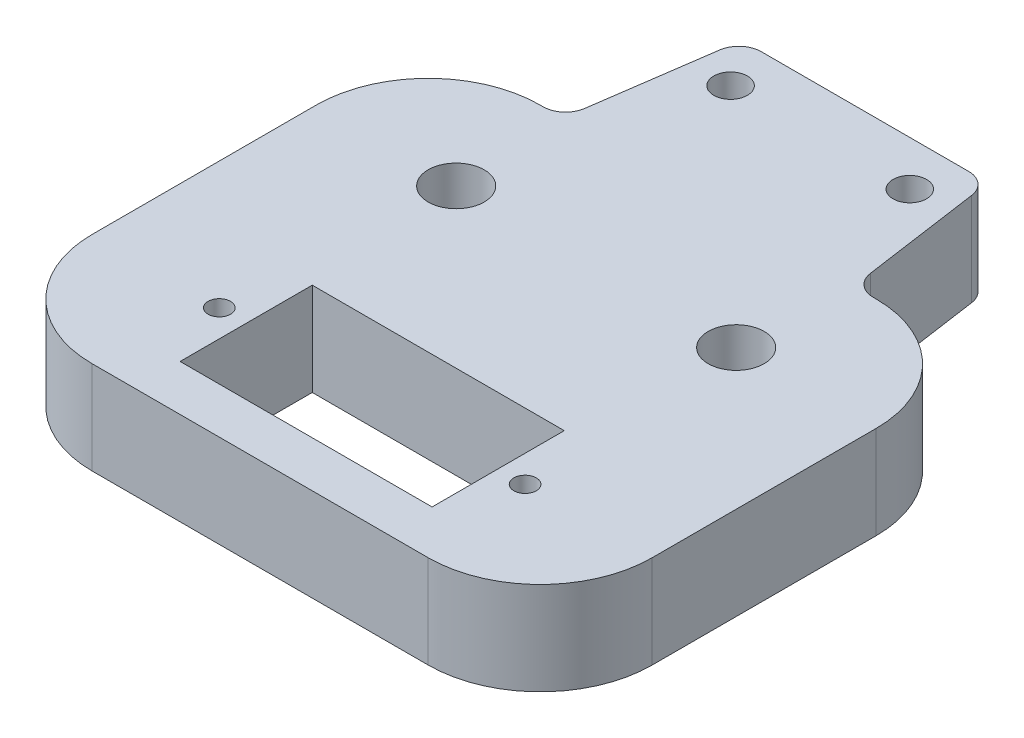
SolidWorks part; units mm, degrees
ref_plane "Front Plane" through (0, 0, 0) normal (0, 0, 1) x (1, 0, 0)
ref_plane "Top Plane" through (0, 0, 0) normal (0, 1, 0) x (1, 0, 0)
ref_plane "Right Plane" through (0, 0, 0) normal (1, 0, 0) x (0, 0, -1)
sketch "Sketch1" plane through (0, 0, 0) normal (0, 1, 0) x (1, 0, 0)
  line L0 (-13, 20) -> (13, 20) construction
  line L1 (-15, 20) -> (-13, 20)
  line L2 (-25, 10) -> (-25, -10)
  line L3 (-15, -20) -> (15, -20)
  line L4 (25, 10) -> (25, -10)
  line L5 (-25, 20) -> (25, -20) construction
  line L6 (-25, -20) -> (25, 20) construction
  line L7 (13, 20) -> (15, 20)
  line L8 (-12.5, 10) -> (12.5, 10) construction
  line L9 (0, -10) -> (0, 0) construction
  line L10 (-11.25, -4.1) -> (11.25, -4.1)
  line L11 (-11.25, -4.1) -> (-11.25, -15.9)
  line L12 (-11.25, -15.9) -> (11.25, -15.9)
  line L13 (11.25, -4.1) -> (11.25, -15.9)
  line L14 (-11.25, -4.1) -> (11.25, -15.9) construction
  line L15 (-11.25, -15.9) -> (11.25, -4.1) construction
  line L16 (-13.65, -10) -> (13.65, -10) construction
  line L17 (0, 34) -> (0, 20) construction
  line L18 (-13, 20) -> (-11, 34)
  line L21 (11, 34) -> (13, 20)
  line L22 (-11, 34) -> (11, 34)
  line L23 (-8, 30) -> (8, 30) construction
  arc A0 (15, -20) -> (25, -10) centre (15, -10) ccw
  arc A1 (15, 20) -> (25, 10) centre (15, 10) cw
  arc A2 (-25, -10) -> (-15, -20) centre (-15, -10) ccw
  arc A3 (-15, 20) -> (-25, 10) centre (-15, 10) ccw
  circle A4 centre (-12.5, 10) radius 2.5
  circle A5 centre (12.5, 10) radius 2.5
  circle A6 centre (13.65, -10) radius 1
  circle A7 centre (-13.65, -10) radius 1
  circle A8 centre (8, 30) radius 1.5
  circle A9 centre (-8, 30) radius 1.5
  point P0 (0, 0)
  point P32 (0, -10)
  point P43 (0, 30)
  point P44 (5, 26)
  dimension "D6" = 10
  dimension "D10" = 5
  dimension "D16" = 2
  dimension "D7" = 3
  dimension "D1" = 50
  dimension "D2" = 40
  dimension "D3" = 2
  dimension "D4" = 14
  dimension "D5" = 22
  dimension "D8" = 10
  dimension "D9" = 16
  dimension "D11" = 25
  dimension "D12" = 22.5
  dimension "D13" = 11.8
  dimension "D14" = 10
  dimension "D15" = 2.4
extrude "Boss-Extrude1" add sketch "Sketch1" along normal blind 8.3
fillet "Fillet1" radius 2 4 edges at (13, 4.15, -20) (11, 4.15, -34) (-13, 4.15, -20) (-11, 4.15, -34)
